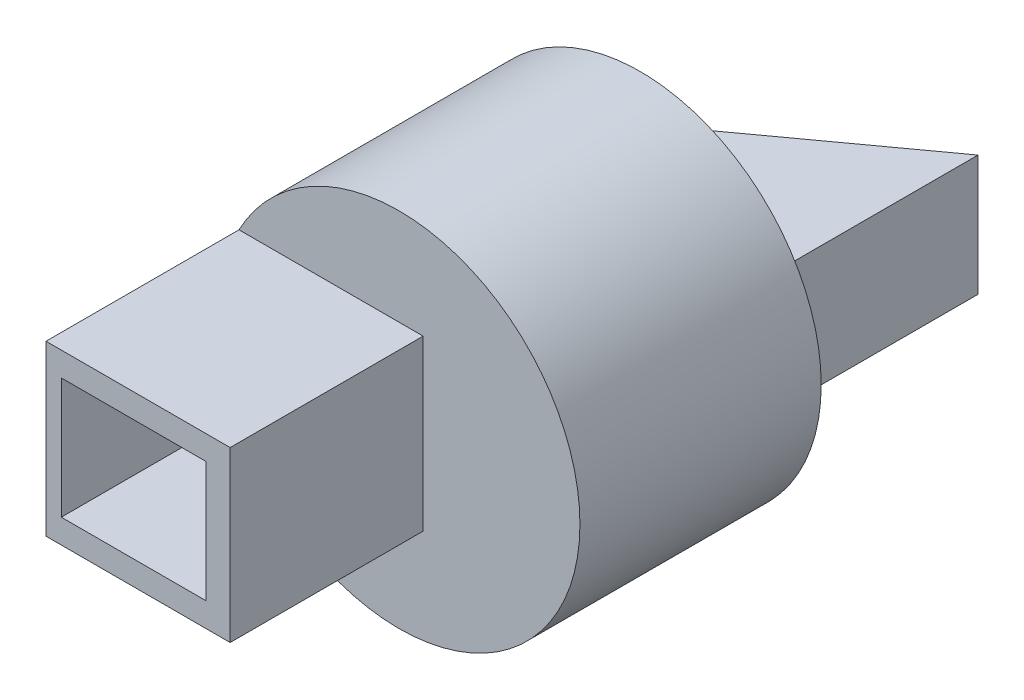
SolidWorks part; units mm, degrees
ref_plane "Alzado" through (0, 0, 0) normal (0, 0, 1) x (1, 0, 0)
ref_plane "Planta" through (0, 0, 0) normal (0, 1, 0) x (1, 0, 0)
ref_plane "Vista lateral" through (0, 0, 0) normal (1, 0, 0) x (0, 0, -1)
sketch "Croquis1" plane through (0, 0, 0) normal (0, 0, 1) x (1, 0, 0)
  line L1 (-48, 23) -> (48, 23)
  line L2 (-48, 23) -> (-48, -23)
  line L3 (-48, -23) -> (48, -23)
  line L4 (48, 23) -> (48, -23)
  line L5 (-50, 25) -> (50, 25)
  line L6 (-50, 25) -> (-50, -25)
  line L7 (-50, -25) -> (50, -25)
  line L8 (50, 25) -> (50, -25)
  point P8 (0, 25)
  point P10 (0, 23)
  point P11 (48, 0)
  point P12 (50, 0)
  dimension "D1" = 100
  dimension "D2" = 50
  dimension "D3" = 2
  dimension "D4" = 2
extrude "Saliente-Extruir1" add sketch "Croquis1" along normal blind 100
sketch "Croquis2" plane through (0, 25, 0) normal (0, 1, 0) x (1, 0, 0)
  line L0 (-50, 0) -> (50, 0)
  line L1 (50, 0) -> (-50, -72.6543)
  line L2 (-50, -100) -> (-50, 0) construction
  line L3 (-50, -72.6543) -> (-50, 0)
  dimension "D1" = 36
extrude "Cortar-Extruir1" cut sketch "Croquis2" against normal blind 100
sketch "Croquis3" plane through (0, 0, 100) normal (0, 0, 1) x (1, 0, 0)
  line L0 (-50, 25) -> (50, 25)
  line L1 (50, 25) -> (50, -25)
  line L2 (50, -25) -> (-50, -25)
  line L3 (-50, -25) -> (-50, 25)
  circle A0 centre (0, 0) radius 75
  dimension "D1" = 150
extrude "Saliente-Extruir2" add sketch "Croquis3" against normal blind 10
sketch "Croquis4" plane through (0, 0, 100) normal (0, 0, 1) x (1, 0, 0)
  circle A0 centre (0, 0) radius 75
  circle A1 centre (0, 0) radius 65
  circle A2 centre (0, 0) radius 75 construction
  dimension "D1" = 10
extrude "Saliente-Extruir3" add sketch "Croquis4" along normal blind 80
sketch "Croquis5" plane through (0, 0, 180) normal (0, 0, 1) x (1, 0, 0)
  line L1 (-60, 25) -> (0, 25)
  line L2 (-60, 25) -> (-60, -25)
  line L3 (-60, -25) -> (0, -25)
  line L4 (0, 25) -> (0, -25)
  circle A0 centre (0, 0) radius 75
  circle A1 centre (0, 0) radius 75 construction
  circle A2 centre (0, 0) radius 65 construction
  point P9 (0, 0)
  point P12 (0, 0)
  dimension "D1" = 60
  dimension "D2" = 50
extrude "Saliente-Extruir4" add sketch "Croquis5" along normal blind 10
sketch "Croquis6" plane through (0, 0, 190) normal (0, 0, 1) x (1, 0, 0)
  line L1 (-60, 25) -> (0, 25)
  line L2 (-60, 25) -> (-60, -25)
  line L3 (-60, -25) -> (0, -25)
  line L4 (0, 25) -> (0, -25)
  line L5 (-66.3325, 35) -> (10, 35)
  line L6 (-66.3325, 35) -> (-66.3325, -35)
  line L7 (-66.3325, -35) -> (10, -35)
  line L8 (10, 35) -> (10, -35)
  circle A0 centre (0, 0) radius 75 construction
  point P12 (0, 0)
  point P13 (12.5524, -31.5901)
  point P14 (0, 0)
  dimension "D1" = 10
  dimension "D2" = 10
extrude "Saliente-Extruir5" add sketch "Croquis6" along normal blind 80
